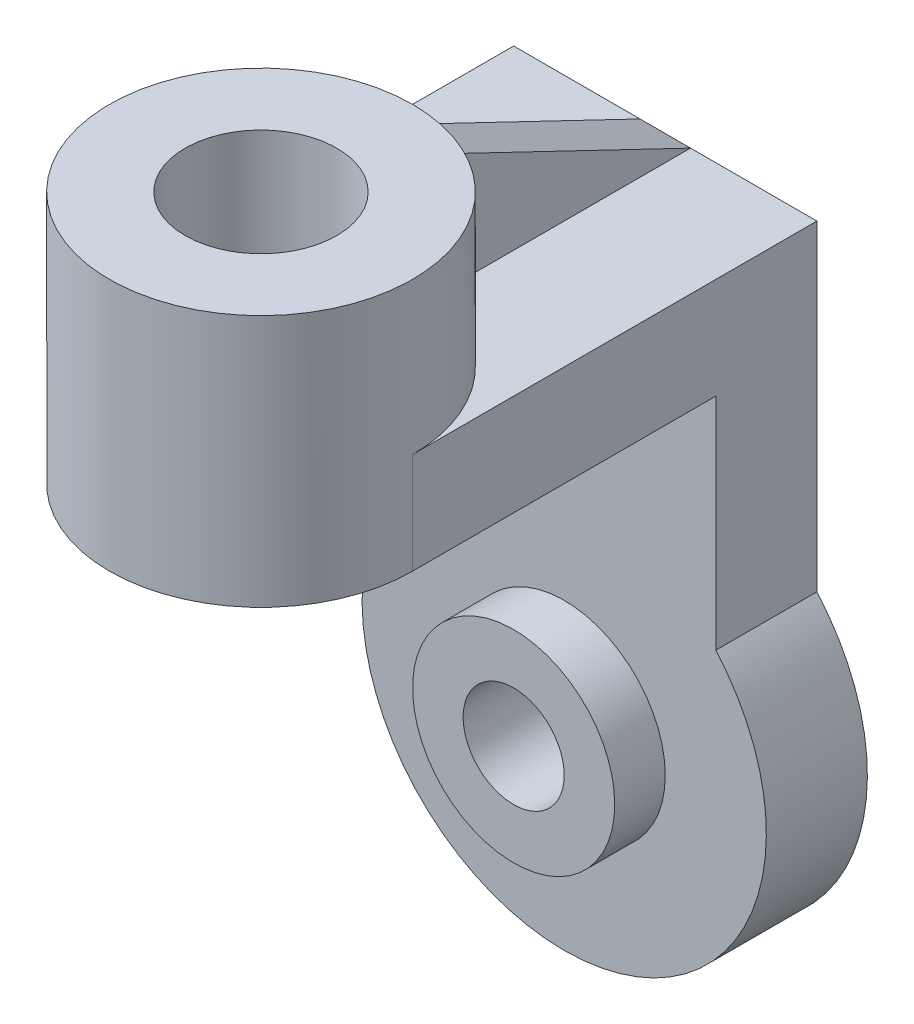
SolidWorks part; units mm, degrees
ref_plane "前视基准面" through (0, 0, 0) normal (0, 0, 1) x (1, 0, 0)
ref_plane "上视基准面" through (0, 0, 0) normal (0, 1, 0) x (1, 0, 0)
ref_plane "右视基准面" through (0, 0, 0) normal (1, 0, 0) x (0, 0, -1)
sketch "草图1" plane through (0, 0, 0) normal (0, 0, 1) x (1, 0, 0)
  line L1 (-15, 35) -> (15, 35)
  line L2 (-15, 35) -> (-15, 13.2288)
  line L4 (15, 35) -> (15, 13.2288)
  arc A0 (-15, 13.2288) -> (15, 13.2288) centre (0, 0) ccw
  dimension "D1" = 40
  dimension "D3" = 30
extrude "凸台-拉伸1" add sketch "草图1" along normal mid plane 10
sketch "草图2" plane through (0, 0, 0) normal (0, 0, 1) x (1, 0, 0)
  circle A0 centre (0, 0) radius 10
  dimension "D1" = 20
extrude "凸台-拉伸2" add sketch "草图2" along normal mid plane 20
sketch "草图3" plane through (0, 0, 10) normal (0, 0, 1) x (1, 0, 0)
  circle A0 centre (0, 0) radius 5
  dimension "D1" = 10
extrude "切除-拉伸1" cut sketch "草图3" against normal blind 20
sketch "草图4" plane through (0, 35, 0) normal (0, 1, 0) x (1, 0, 0)
  line L1 (-15, 5) -> (15, 5)
  line L2 (-15, 5) -> (-15, -35)
  line L3 (-15, -35) -> (15, -35)
  line L4 (15, 5) -> (15, -35)
  dimension "D1" = 40
extrude "凸台-拉伸3" add sketch "草图4" along normal blind 10
sketch "草图5" plane through (0, 35, 0) normal (0, -1, 0) x (1, 0, 0)
  line L0 (-15, 35) -> (15, 35) construction
  circle A0 centre (0, 35) radius 15
  dimension "D1" = 30
extrude "凸台-拉伸4" add sketch "草图5" against normal blind 25
sketch "草图6" plane through (0, 60, 0) normal (0, 1, 0) x (1, 0, 0)
  circle A0 centre (0, -35) radius 7.5
  dimension "D1" = 15
extrude "切除-拉伸2" cut sketch "草图6" against normal blind 25
sketch "草图7" plane through (0, 0, 0) normal (1, 0, 0) x (0, 0, -1)
  line L0 (5, 45) -> (-20, 57)
  line L1 (-20, 45) -> (-20, 60) construction
  dimension "D1" = 3
rib "筋3" sketch "草图7" sketch "草图7" thickness 5 extrusion direction parallel to sketch draft on no parameters "D1"=5
